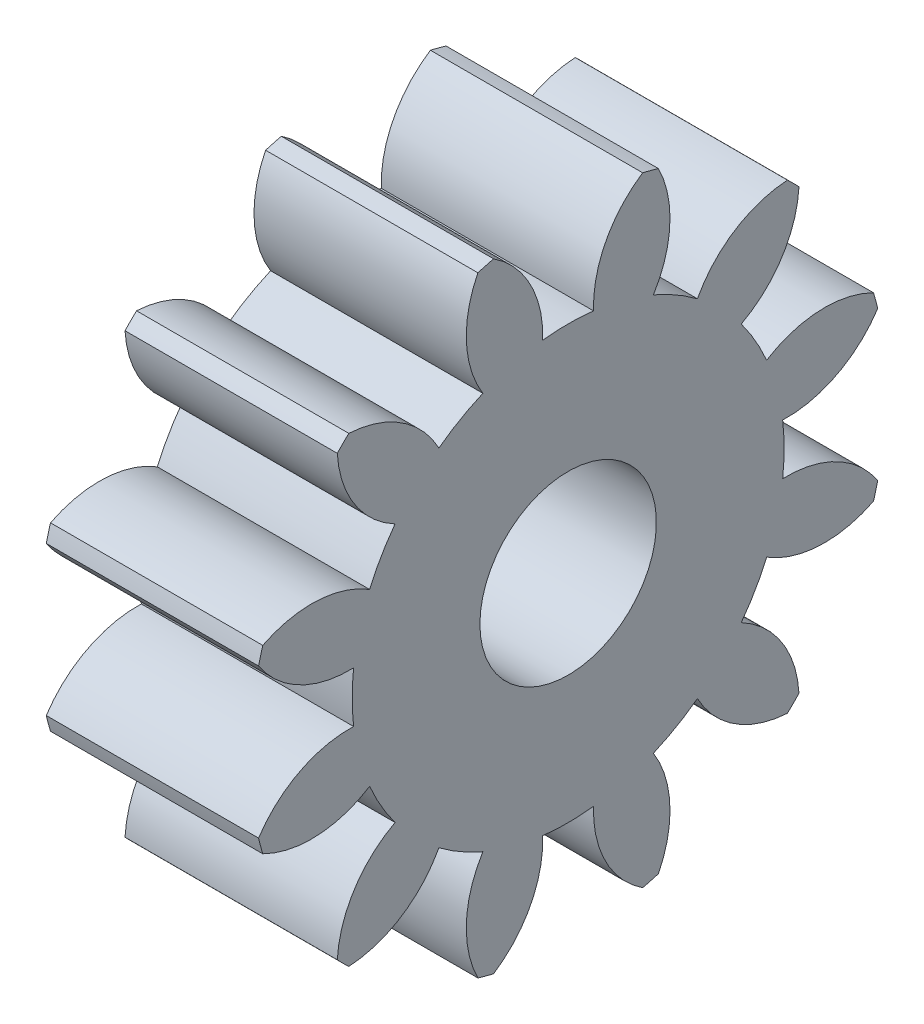
SolidWorks part; units mm, degrees
ref_plane "Plane1" through (0, 0, 0) normal (0, 0, 1) x (1, 0, 0)
ref_plane "Plane2" through (0, 0, 0) normal (0, 1, 0) x (1, 0, 0)
ref_plane "Plane3" through (0, 0, 0) normal (1, 0, 0) x (0, 0, -1)
sketch "HoldingSke" plane through (0, 0, 0) normal (0, 1, 0) x (1, 0, 0)
  line L0 (0, 0) -> (0.6521, -0.1386)
  line L1 (-15, 0) -> (100, 0) construction
  line L2 (0, 0) -> (-2.1039, 2.3779)
  line L3 (0, 0) -> (-11.863, 4.5341)
  line L4 (0, 0) -> (8.4473, 1.7955)
  line L5 (0, 0) -> (-46.8476, -17.4728)
  line L6 (0, 0) -> (-5.8027, -3.9151)
  line L7 (-2.1039, 2.3779) -> (8.6586, 51.2059)
  line L8 (-76.2, 54.61) -> (-75.3, 54.61)
  line L9 (-71.009, 38.7566) -> (-53.1078, 45.2721)
  line L10 (-76.2, 71.12) -> (104.1128, 71.12)
  line L11 (0, 0) -> (-7, 0)
  line L12 (-76.2, 101.6) -> (-76.147, 101.6)
  line L13 (24.9733, 27.94) -> (52.9518, 28.4284)
  line L14 (24.9733, 27.94) -> (24.9743, 27.94)
  line L15 (24.9733, 27.94) -> (100.4006, 29.5858)
  line L16 (-63.627, -1.5) -> (-12.827, -1.5)
  circle A0 centre (0, 0) radius 2.5
  circle A1 centre (0, 0) radius 7.124
  circle A2 centre (0, 0) radius 37.5
  circle A3 centre (0, 0) radius 2.5
  dimension "MHD" = 14.248
  dimension "Hub_dia" = 75
  dimension "Bore" = 5
  dimension "MBD" = 5
  dimension "Num_teeth" = 12
  dimension "Pitch" = 0.6667
  dimension "Overall_len" = 50
  dimension "Show_teeth" = 12
  dimension "Thickness" = 7
  dimension "OAL" = 50.0001
  dimension "T_dim" = 0.9
  dimension "Ap" = 20
  dimension "H" = 19.05
  dimension "Pitch_radius" = 180.3128
  dimension "Width" = 7
  dimension "Backlash" = 0.053
  dimension "Addendum_fac" = 1
  dimension "Dedendum_fac" = 1.25
  dimension "Clearance_fac" = 0.25
  dimension "Dedendum_add" = 0.001
  dimension "Module" = 1.5
sketch "BasProSke" plane through (0, 0, 0) normal (0, 1, 0) x (1, 0, 0)
  line L0 (-10, 0) -> (60, 0) construction
  line L1 (0, 0) -> (0, 10.5)
  line L2 (0, 0) -> (7, 0)
  line L3 (7, 0) -> (7, 10.5)
  line L4 (7, 10.5) -> (0, 10.5)
  dimension "Thickness" = 7
  dimension "Diameter" = 21
revolve "Base-Revolve" add sketch "BasProSke" angle 360 about L0
sketch "TooCutSke" plane through (0, 0, 0) normal (1, 0, 0) x (0, 0, -1)
  line L1 (0, 0) -> (0, 107) construction
  line L2 (0, 0) -> (-1.2674, 8.9103) construction
  line L3 (0, 0) -> (-4.625, 17.2606) construction
  line L4 (-1.2674, 8.9103) -> (-2.3125, 8.6303) construction
  arc A0 (0.8378, 7.0746) -> (-0.8378, 7.0746) centre (0, 0) ccw
  arc A1 (2.4865, 10.2275) -> (-2.4865, 10.2275) centre (0, 0) ccw
  circle A2 centre (0, 0) radius 9 construction
  circle A3 centre (0, 0) radius 8.4572 construction
  arc A4 (-0.8378, 7.0746) -> (-2.4865, 10.2275) centre (-4.4355, 7.2007) ccw
  arc A5 (2.4865, 10.2275) -> (0.8378, 7.0746) centre (4.4355, 7.2007) ccw
  dimension "Root_dia" = 14.248
  dimension "Overcut_dia" = 21.0508
  dimension "Pitch_dia" = 18
  dimension "Base_dia" = 16.9145
  dimension "Flank_rad" = 3.6
  dimension "Half_ang" = 15
  dimension "Half_CT" = 1.082
extrude "ToothCut" cut sketch "TooCutSke" along normal through all
fillet "Breaks" [suppressed] radius 0.03
fillet "RootFillets" [suppressed] radius 0.376
pattern_circular "TeethCuts" count 12 every 30 about axis through (-10, 0, 0) along (1, 0, 0) of "ToothCut", "RootFillets", "Breaks"
sketch "HubNeaOneSke" plane through (0, 0, 0) normal (-1, 0, 0) x (0, 0, 1)
  circle A0 centre (0, 0) radius 7.124
  dimension "Diameter" = 14.248
extrude "HubNearOne" [suppressed] add sketch "HubNeaOneSke" along normal blind 43.0001
sketch "HubNeaBotSke" plane through (0, 0, 0) normal (-1, 0, 0) x (0, 0, 1)
  circle A0 centre (0, 0) radius 7.124
  dimension "Diameter" = 14.248
extrude "HubNearBoth" [suppressed] add sketch "HubNeaBotSke" along normal blind 21.5
ref_plane "FarPln" through (7, 0, 0) normal (1, 0, 0) x (0, 0, -1)
sketch "HubFarSke" plane through (7, 0, 0) normal (1, 0, 0) x (0, 0, -1)
  circle A0 centre (0, 0) radius 7.124
  dimension "Diameter" = 14.248
extrude "HubFar" [suppressed] add sketch "HubFarSke" along normal blind 21.5
sketch "BorSke" plane through (0, 0, 0) normal (1, 0, 0) x (0, 0, -1)
  circle A0 centre (0, 0) radius 2.5
  dimension "Diameter" = 5
extrude "Bore" cut sketch "BorSke" along normal mid plane 100.0001
sketch "KeySke" plane through (0, 0, 0) normal (1, 0, 0) x (0, 0, -1)
  line L0 (-1, 0) -> (-1, 3.4)
  line L1 (-1, 3.4) -> (1, 3.4)
  line L2 (1, 3.4) -> (1, 0)
  line L3 (0, 0) -> (0, 34) construction
  line L4 (-1, 0) -> (1, 0)
  dimension "Offset" = 3.4
  dimension "Width" = 2
extrude "Keyway" [suppressed] cut sketch "KeySke" along normal mid plane 100.0001
pattern_circular "Keyway2" [suppressed] count 2 every 90 about axis through (-10, 0, 0) along (1, 0, 0)
sketch "Croquis2" plane through (0, 0, 0) normal (-1, 0, 0) x (0, 0, 1)
  circle A0 centre (0, 0) radius 2.91
  dimension "D1" = 5.82
extrude "Cortar-Extruir1" cut sketch "Croquis2" against normal blind 11
ref_plane "Plano1" through (1, 0, 0) normal (1, 0, 0) x (0, 0, -1)
sketch "Croquis3" plane through (1, 0, 0) normal (1, 0, 0) x (0, 0, -1)
  circle A0 centre (0, 0) radius 3.2524
  circle A1 centre (0, 0) radius 1.9
  dimension "D1" = 3.8
extrude "Saliente-Extruir2" add sketch "Croquis3" along normal mid plane 1.58
equation "' \"Module@HoldingSke\" = 6.35"
equation "' \"Num_teeth@HoldingSke\" = 12"
equation "' \"Ap@HoldingSke\" =  20"
equation "' \"Ap@HoldingSke\" = 20"
equation "' \"Width@HoldingSke\" = 0.5 * 25.4"
equation "' \"Hub_dia@HoldingSke\"= 1 * 25.4"
equation "' \"Hub_dia@HoldingSke\" = 1 * 25.4"
equation "' \"Overall_len@HoldingSke\" = 1.0 * 25.4"
equation "' \"Bore@HoldingSke\" = 0.75 * 25.4"
equation "' \"T_dim@HoldingSke\" = 0.1 * 25.4"
equation "' \"Width@KeySke\" = 0.25 * 25.4"
equation "' \"Show_teeth@HoldingSke\" = 13"
equation "' \"Backlash@HoldingSke\" = 0.009 * 25.4"
equation "' \"Addendum_fac@HoldingSke\" = 1.0"
equation "' \"Dedendum_fac@HoldingSke\" = 1.25"
equation "' \"Dedendum_add@HoldingSke\" = 0.00005 * 25.4"
equation "' \"Clearance_fac@HoldingSke\" = 0.25"
equation "\"Pitch@HoldingSke\" = 1 / \"Module@HoldingSke\""
equation "\"Overcut_dia@TooCutSke\" = (\"Num_teeth@HoldingSke\" + 2 * \"Addendum_fac@HoldingSke\") / \"Pitch@HoldingSke\" + 0.002 * 25.4"
equation "\"Pitch_dia@TooCutSke\" = \"Num_teeth@HoldingSke\" / \"Pitch@HoldingSke\""
equation "\"Base_dia@TooCutSke\" = \"Num_teeth@HoldingSke\" / \"Pitch@HoldingSke\" * cos((\"Ap@HoldingSke\"  * 3.14159265 / 180))"
equation "\"Root_dia@TooCutSke\" = (\"Num_teeth@HoldingSke\" + 2) / \"Pitch@HoldingSke\" - 2 * (\"Addendum_fac@HoldingSke\" + \"Dedendum_fac@HoldingSke\") / \"Pitch@HoldingSke\" - \"Dedendum_add@HoldingSke\" * 2"
equation "\"Half_ang@TooCutSke\" = 180 / \"Num_teeth@HoldingSke\""
equation "\"Half_CT@TooCutSke\" = \"Num_teeth@HoldingSke\" / \"Pitch@HoldingSke\" * sin((3.14159265 / 2 / \"Num_teeth@HoldingSke\")) / 2 - 7 * \"Backlash@HoldingSke\" / 4"
equation "\"Flank_rad@TooCutSke\" = \"Num_teeth@HoldingSke\" / \"Pitch@HoldingSke\" / 5"
equation "\"Radius@RootFillets\" = \"Clearance_fac@HoldingSke\" / \"Pitch@HoldingSke\" + \"Dedendum_add@HoldingSke\""
equation "\"Break_rad@Breaks\" = 0.02 / \"Pitch@HoldingSke\""
equation "\"Thickness@HoldingSke\" = \"Width@HoldingSke\""
equation "\"OAL@HoldingSke\" = \"Thickness@HoldingSke\""
equation "\"MHD@HoldingSke\" = (\"Num_teeth@HoldingSke\" + 2) / \"Pitch@HoldingSke\" - 2 * (\"Addendum_fac@HoldingSke\" + \"Dedendum_fac@HoldingSke\")  / \"Pitch@HoldingSke\" - \"Dedendum_add@HoldingSke\" * 2"
equation "\"MBD@HoldingSke\" = (\"Num_teeth@HoldingSke\" + 2) / \"Pitch@HoldingSke\" - 2 * (\"Addendum_fac@HoldingSke\" + \"Dedendum_fac@HoldingSke\")  / \"Pitch@HoldingSke\" - \"Dedendum_add@HoldingSke\" * 2 - 0.002 * 25.4"
equation "\"MHD@HoldingSke\" = ((sgn( \"MHD@HoldingSke\" - \"Hub_dia@HoldingSke\" )-1)*( \"MHD@HoldingSke\" - \"Hub_dia@HoldingSke\" ))/-2+ \"Hub_dia@HoldingSke\""
equation "\"MBD@HoldingSke\" = ((sgn( \"MBD@HoldingSke\" - \"Bore@HoldingSke\" )-1)*( \"MBD@HoldingSke\" - \"Bore@HoldingSke\" ))/-2+ \"Bore@HoldingSke\""
equation "\"OAL@HoldingSke\" = ((sgn( \"OAL@HoldingSke\" - \"Overall_len@HoldingSke\" )+1)*( \"OAL@HoldingSke\" - \"Overall_len@HoldingSke\" ))/2 + \"Overall_len@HoldingSke\" + 0.000002 * 25.4"
equation "\"Num_teeth@TeethCuts\" = int( \"Show_teeth@HoldingSke\" ) + 1"
equation "\"Num_teeth@TeethCuts\" = ((sgn( \"Num_teeth@TeethCuts\" - \"Num_teeth@HoldingSke\" )-1)*( \"Num_teeth@TeethCuts\" - \"Num_teeth@HoldingSke\" ))/-2+ \"Num_teeth@HoldingSke\""
equation "\"Num_teeth@TeethCuts\" = ((sgn( \"Num_teeth@TeethCuts\" - 2.0)+1)*( \"Num_teeth@TeethCuts\" - 2.0))/2 +2.0"
equation "\"Angle@TeethCuts\" = 360.0 / \"Num_teeth@HoldingSke\""
equation "\"Diameter@BasProSke\" = (\"Num_teeth@HoldingSke\" + 2 * \"Addendum_fac@HoldingSke\") / \"Pitch@HoldingSke\""
equation "\"Thickness@BasProSke\"  = \"Thickness@HoldingSke\""
equation "' \"Fillet_rad@BasProSke\" =  \"Thickness@HoldingSke\" * 0.05"
equation "' \"Fillet_rad@BasProSke\" = \"Thickness@HoldingSke\" * 0.05"
equation "\"MHD@HoldingSke\" = ((sgn( \"MHD@HoldingSke\" - \"Root_dia@TooCutSke\" )-1)*( \"MHD@HoldingSke\" - \"Root_dia@TooCutSke\" ))/-2+ \"Root_dia@TooCutSke\""
equation "\"Diameter@HubNeaOneSke\" = \"MHD@HoldingSke\""
equation "\"Length@HubNearOne\" = \"OAL@HoldingSke\" - \"Thickness@BasProSke\""
equation "\"Diameter@HubNeaBotSke\" = \"MHD@HoldingSke\""
equation "\"Length@HubNearBoth\" = ( \"OAL@HoldingSke\" - \"Thickness@BasProSke\" ) / 2.0"
equation "\"Thickness@FarPln\" = \"Thickness@BasProSke\""
equation "\"Diameter@HubFarSke\" = \"MHD@HoldingSke\""
equation "\"Length@HubFar\" = ( \"OAL@HoldingSke\" - \"Thickness@BasProSke\" ) / 2.0"
equation "\"Diameter@BorSke\" = \"MBD@HoldingSke\""
equation "\"D1@Bore\" = \"OAL@HoldingSke\" * 2.0"
equation "\"D1@Keyway\" = \"OAL@HoldingSke\" * 2.0"
equation "\"Offset@KeySke\" = \"T_dim@HoldingSke\" + \"MBD@HoldingSke\" / 2.0"
